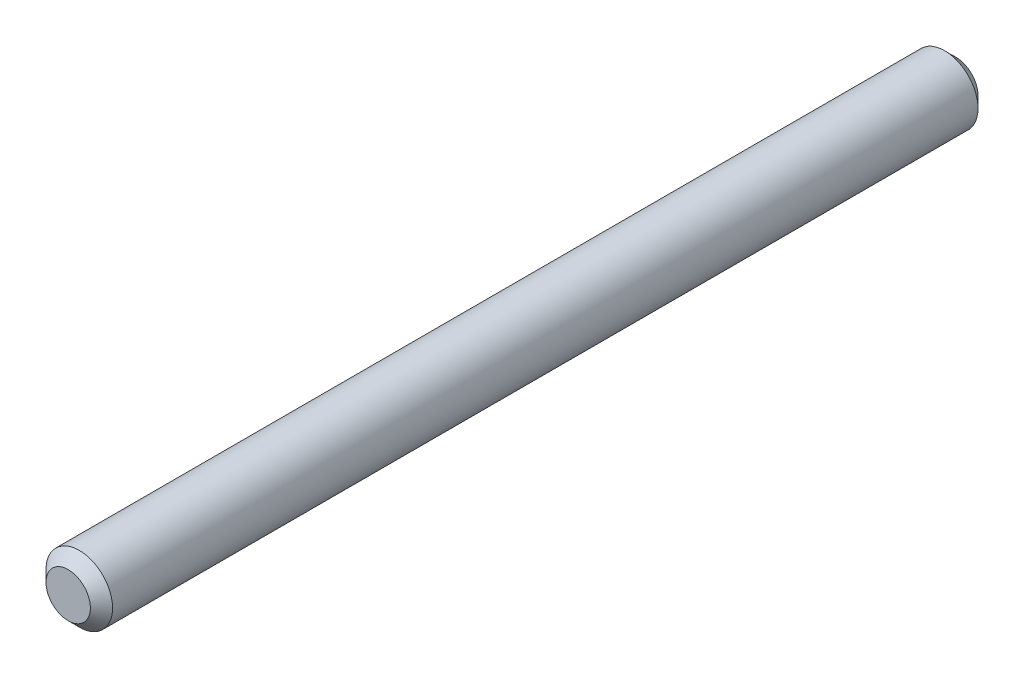
SolidWorks part; units mm, degrees
ref_plane "Płaszczyzna przednia" through (0, 0, 0) normal (0, 0, 1) x (1, 0, 0)
ref_plane "Płaszczyzna górna" through (0, 0, 0) normal (0, 1, 0) x (1, 0, 0)
ref_plane "Płaszczyzna prawa" through (0, 0, 0) normal (1, 0, 0) x (0, 0, -1)
sketch "Szkic1" plane through (0, 0, 0) normal (0, 0, 1) x (1, 0, 0)
  circle A0 centre (0, 0) radius 3
  dimension "D1" = 6
extrude "Dodanie-wyciągnięcie1" add sketch "Szkic1" along normal mid plane 80
chamfer "Sfazowanie1" distance 1 angle 45 2 edges at (3, 0, -40) (3, 0, 40)
